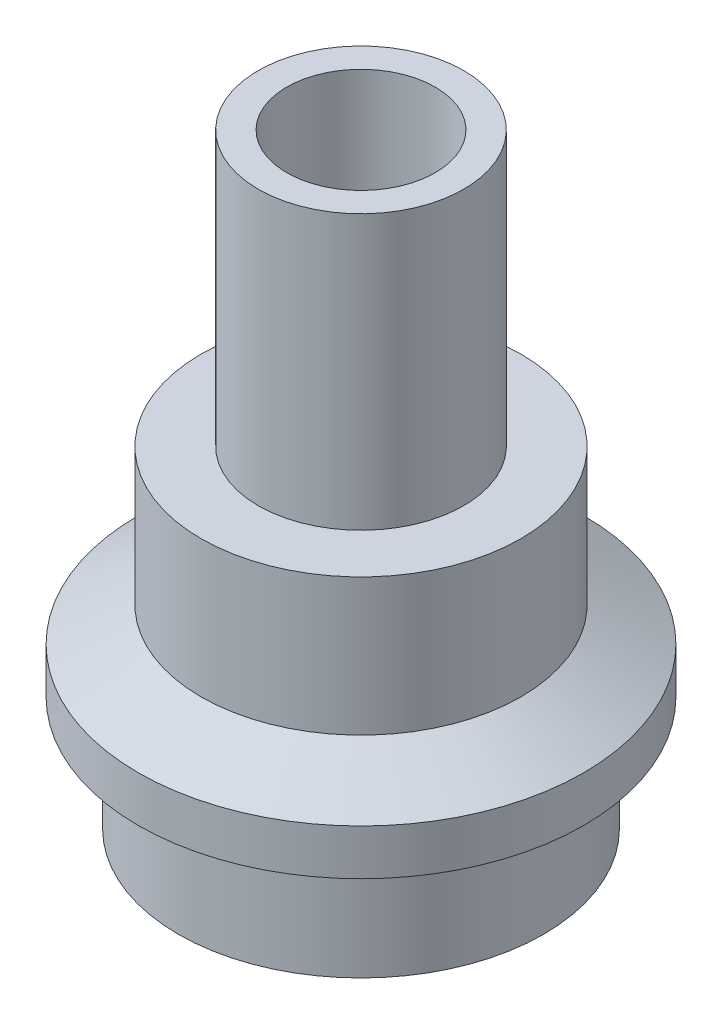
SolidWorks part; units mm, degrees
ref_plane "Front Plane" through (0, 0, 0) normal (0, 0, 1) x (1, 0, 0)
ref_plane "Top Plane" through (0, 0, 0) normal (0, 1, 0) x (1, 0, 0)
ref_plane "Right Plane" through (0, 0, 0) normal (1, 0, 0) x (0, 0, -1)
sketch "Sketch1" plane through (0, 0, 0) normal (0, 0, 1) x (1, 0, 0)
  line L0 (11, 0) -> (16, 0)
  line L1 (16, 0) -> (16, 10)
  line L2 (16, 10) -> (19.5, 10)
  line L3 (19.5, 10) -> (19.5, 14)
  line L4 (19.5, 14) -> (14, 17)
  line L5 (14, 17) -> (14, 29)
  line L6 (14, 29) -> (9, 29)
  line L7 (9, 29) -> (9, 53)
  line L8 (9, 53) -> (6.5, 53)
  line L9 (6.5, 53) -> (6.5, 41)
  line L10 (6.5, 41) -> (3, 40)
  line L11 (3, 40) -> (3, 38)
  line L12 (3, 38) -> (3.5, 38)
  line L13 (3.5, 38) -> (3.5, 11)
  line L14 (3.5, 11) -> (11, 11)
  line L15 (11, 11) -> (11, 0)
  line L16 (0, 0) -> (0, 33.0142) construction
  dimension "D1" = 11
  dimension "D2" = 7
  dimension "D3" = 16
  dimension "D4" = 19.5
  dimension "D5" = 10
  dimension "D6" = 11
  dimension "D7" = 4
  dimension "D8" = 28
  dimension "D9" = 18
  dimension "D10" = 27
  dimension "D11" = 53
  dimension "D12" = 12
  dimension "D13" = 3
  dimension "D14" = 13
  dimension "D15" = 6
  dimension "D16" = 1
  dimension "D17" = 2
revolve "Revolve1" add sketch "Sketch1" angle 360 about L16
cosmetic thread "Cosmetic Thread1" parameters "D2"=26.158
cosmetic thread "Cosmetic Thread2" parameters "D1"=12, "D2"=15.252
cosmetic thread "Cosmetic Thread3" parameters "D2"=12
